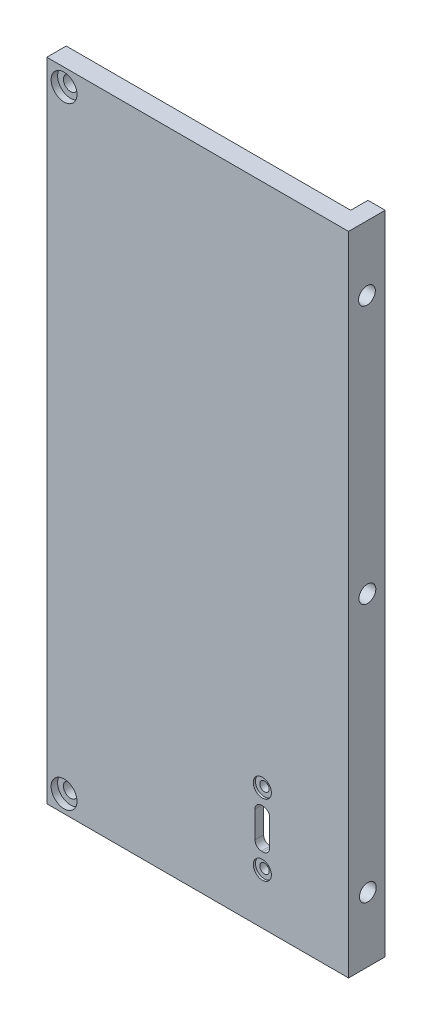
SolidWorks part; units mm, degrees
ref_plane "Front Plane" through (0, 0, 0) normal (1, 0, 0) x (0, 1, 0)
ref_plane "Top Plane" through (0, 0, 0) normal (0, 0, 1) x (0, 1, 0)
ref_plane "Right Plane" through (0, 0, 0) normal (0, 1, 0) x (-1, 0, 0)
sketch "Sketch1" plane through (0, 0, 0) normal (0, 0, 1) x (0, 1, 0)
  line L1 (0, 0) -> (150, 0)
  line L2 (0, 0) -> (0, 70)
  line L3 (0, 70) -> (150, 70)
  line L4 (150, 0) -> (150, 70)
  dimension "D1" = 150
  dimension "D2" = 70
extrude "Boss-Extrude1" add sketch "Sketch1" along normal blind 4.5
sketch "Sketch7" plane through (0, 0, 0) normal (0, 0, -1) x (1, 0, 0)
  line L0 (-70, 0) -> (0, 0) construction
  line L1 (-4, 0) -> (0, 0)
  line L2 (-4, 0) -> (-4, -150)
  line L3 (-4, -150) -> (0, -150)
  line L4 (0, 0) -> (0, -150)
  dimension "D1" = 4
extrude "Boss-Extrude2" add sketch "Sketch7" along normal blind 4
sketch "Sketch8" plane through (0, 0, 0) normal (1, 0, 0) x (0, 1, 0)
  line L0 (0, 0) -> (150, 0.25) construction
  line L1 (150, 4.5) -> (150, -4) construction
  line L2 (0, 4.5) -> (0, -4) construction
  circle A0 centre (15, 0.025) radius 1.95
  circle A1 centre (75, 0.125) radius 1.95
  circle A2 centre (135, 0.225) radius 1.95
  dimension "D1" = 3.9
  dimension "D2" = 15
  dimension "D3" = 15
extrude "Cut-Extrude5" cut sketch "Sketch8" against normal blind 10
sketch "Sketch9" plane through (0, 0, 4.5) normal (0, 0, 1) x (1, 0, 0)
  line L0 (-66, 150) -> (-66, 0) construction
  line L1 (0, 150) -> (-70, 150) construction
  line L2 (-70, 0) -> (0, 0) construction
  line L3 (-70, 150) -> (-70, 0) construction
  circle A0 centre (-66, 146) radius 1.65
  circle A1 centre (-66, 4) radius 1.65
  dimension "D1" = 3.3
  dimension "D2" = 4
  dimension "D3" = 4
  dimension "D4" = 4
extrude "Cut-Extrude6" cut sketch "Sketch9" against normal through all
sketch "Sketch10" plane through (0, 0, 4.5) normal (0, 0, 1) x (1, 0, 0)
  circle A0 centre (-66, 146) radius 3
  circle A1 centre (-66, 4) radius 3
  dimension "D1" = 6
extrude "Cut-Extrude7" cut sketch "Sketch10" against normal blind 1.5
sketch "Sketch13" plane through (0, 0, 4.5) normal (0, 0, 1) x (1, 0, 0)
  line L0 (-20, 0) -> (-20, 150) construction
  line L1 (-70, 0) -> (0, 0) construction
  line L2 (0, 150) -> (-70, 150) construction
  line L3 (0, 0) -> (0, 150) construction
  circle A0 centre (-20, 28.25) radius 2.1
  circle A1 centre (-20, 11.75) radius 2.1
  dimension "D4" = 4.2
  dimension "D1" = 20
  dimension "D2" = 16.5
  dimension "D3" = 11.75
extrude "Cut-Extrude10" cut sketch "Sketch13" against normal blind 0.5
sketch "Sketch14" plane through (0, 0, 4.5) normal (0, 0, 1) x (1, 0, 0)
  line L0 (-20, 28.25) -> (-20, 11.75) construction
  line L2 (-21.7, 24.6) -> (-18.3, 24.6)
  line L3 (-21.7, 24.6) -> (-21.7, 15.4)
  line L4 (-21.7, 15.4) -> (-18.3, 15.4)
  line L5 (-18.3, 24.6) -> (-18.3, 15.4)
  line L6 (-21.7, 24.6) -> (-18.3, 15.4) construction
  line L7 (-21.7, 15.4) -> (-18.3, 24.6) construction
  circle A0 centre (-20, 11.75) radius 1.1
  circle A1 centre (-20, 28.25) radius 1.1
  point P4 (-20, 20)
  dimension "D1" = 2.2
  dimension "D2" = 3.4
  dimension "D3" = 9.2
extrude "Cut-Extrude11" cut sketch "Sketch14" against normal through all
fillet "Fillet3" radius 1.5 4 edges at (-18.3, 15.4, 2.25) (-21.7, 15.4, 2.25) (-21.7, 24.6, 2.25) (-18.3, 24.6, 2.25)
sketch "Sketch15" plane through (0, 0, 0) normal (0, 0, -1) x (1, 0, 0)
  line L0 (-20, -11.75) -> (-20, -28.25) construction
  line L2 (-26, -6.5) -> (-14, -6.5)
  line L3 (-26, -6.5) -> (-26, -33.5)
  line L4 (-26, -33.5) -> (-14, -33.5)
  line L5 (-14, -6.5) -> (-14, -33.5)
  line L6 (-26, -6.5) -> (-14, -33.5) construction
  line L7 (-26, -33.5) -> (-14, -6.5) construction
  point P4 (-20, -20)
  dimension "D1" = 27
  dimension "D2" = 12
extrude "Cut-Extrude12" cut sketch "Sketch15" against normal blind 2.5
fillet "Fillet4" radius 4 4 edges at (-14, 6.5, 1.25) (-26, 6.5, 1.25) (-26, 33.5, 1.25) (-14, 33.5, 1.25)
